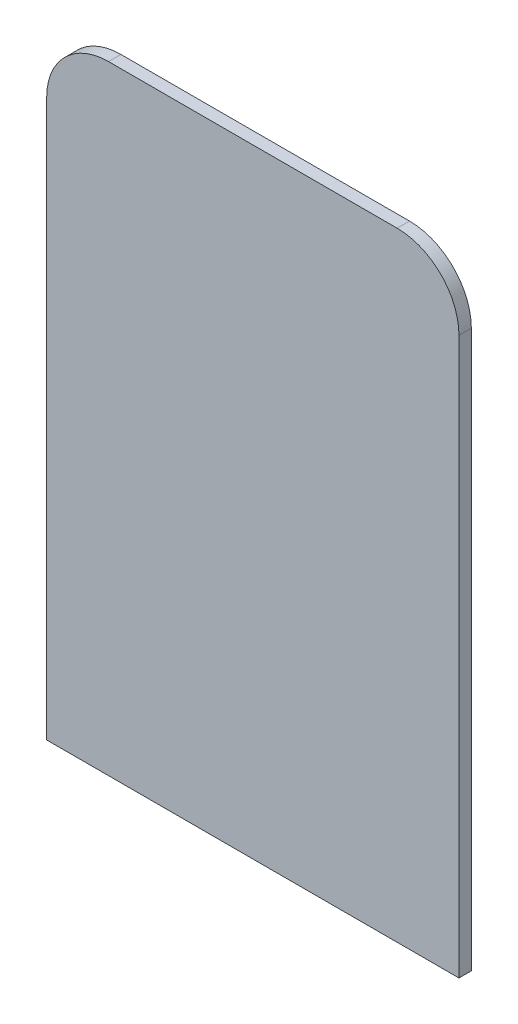
SolidWorks part; units mm, degrees
material "Acrylic (Medium-high impact)"
ref_plane "Front Plane" through (0, 0, 0) normal (0, 0, 1) x (1, 0, 0)
ref_plane "Top Plane" through (0, 0, 0) normal (0, 1, 0) x (1, 0, 0)
ref_plane "Right Plane" through (0, 0, 0) normal (1, 0, 0) x (0, 0, -1)
sketch "Sketch1" [suppressed] plane through (0, 0, 0) normal (0, 1, 0) x (1, 0, 0)
  line L1 (-60, -30) -> (60, -30)
  line L2 (-60, -30) -> (-60, 30)
  line L3 (-60, 30) -> (60, 30)
  line L4 (60, -30) -> (60, 30)
  line L5 (-60, -30) -> (60, 30) construction
  line L6 (-60, 30) -> (60, -30) construction
  point P0 (0, 0)
  dimension "D1" = 120
  dimension "D2" = 60
extrude "Boss-Extrude1" [suppressed] add sketch "Sketch1" along normal blind 3
sketch "Sketch2" [suppressed] plane through (0, 0, 0) normal (1, 0, 0) x (0, 0, -1)
  line L1 (-25, 7.5) -> (25, 7.5)
  line L2 (-25, 7.5) -> (-25, -7.5)
  line L3 (-25, -7.5) -> (25, -7.5)
  line L4 (25, 7.5) -> (25, -7.5)
  line L5 (-25, 7.5) -> (25, -7.5) construction
  line L6 (-25, -7.5) -> (25, 7.5) construction
  point P0 (0, 0)
  dimension "D1" = 60
  dimension "D2" = 15
extrude "Boss-Extrude2" [suppressed] add sketch "Sketch2" along normal blind 3
sketch "Sketch3" [suppressed] plane through (0, 3, 0) normal (0, 1, 0) x (1, 0, 0)
  line L0 (60, 30) -> (-60, 30) construction
  line L1 (-52, 30) -> (-43, 30)
  line L2 (-52, 30) -> (-52, 27)
  line L3 (-52, 27) -> (-43, 27)
  line L4 (-43, 30) -> (-43, 27)
  line L5 (-60, 30) -> (-60, -30) construction
  line L6 (-33, 30) -> (-24, 30)
  line L7 (-33, 30) -> (-33, 27)
  line L8 (-33, 27) -> (-24, 27)
  line L9 (-24, 30) -> (-24, 27)
  line L10 (-33, -27) -> (-24, -27)
  line L11 (-33, -27) -> (-33, -30)
  line L12 (-33, -30) -> (-24, -30)
  line L13 (-24, -27) -> (-24, -30)
  line L14 (-52, -27) -> (-43, -27)
  line L15 (-52, -27) -> (-52, -30)
  line L16 (-52, -30) -> (-43, -30)
  line L17 (-43, -27) -> (-43, -30)
  line L18 (-60, -30) -> (60, -30) construction
  line L43 (-14, 30) -> (-5, 30)
  line L44 (-14, 30) -> (-14, 27)
  line L45 (-14, 27) -> (-5, 27)
  line L46 (-5, 30) -> (-5, 27)
  line L47 (5, 30) -> (14, 30)
  line L48 (5, 30) -> (5, 27)
  line L49 (5, 27) -> (14, 27)
  line L50 (14, 30) -> (14, 27)
  line L51 (24, 30) -> (33, 30)
  line L52 (24, 30) -> (24, 27)
  line L53 (24, 27) -> (33, 27)
  line L54 (33, 30) -> (33, 27)
  line L59 (-14, -27) -> (-5, -27)
  line L60 (-14, -27) -> (-14, -30)
  line L61 (-14, -30) -> (-5, -30)
  line L62 (-5, -27) -> (-5, -30)
  line L63 (5, -27) -> (14, -27)
  line L64 (5, -27) -> (5, -30)
  line L65 (5, -30) -> (14, -30)
  line L66 (14, -27) -> (14, -30)
  line L67 (24, -27) -> (33, -27)
  line L68 (24, -27) -> (24, -30)
  line L69 (24, -30) -> (33, -30)
  line L70 (33, -27) -> (33, -30)
  line L71 (43, 30) -> (52, 30)
  line L72 (43, 30) -> (43, 27)
  line L73 (43, 27) -> (52, 27)
  line L74 (52, 30) -> (52, 27)
  line L83 (43, -27) -> (52, -27)
  line L84 (43, -27) -> (43, -30)
  line L85 (43, -30) -> (52, -30)
  line L86 (52, -27) -> (52, -30)
  line L105 (60, -30) -> (60, 30) construction
  dimension "D1" = 8
  dimension "D2" = 9
  dimension "D5" = 3
  dimension "D6" = 10
  dimension "D7" = 8
  dimension "D3" = 6
  dimension "D4" = 2
extrude "Cut-Extrude1" [suppressed] cut sketch "Sketch3" against normal blind 3
sketch "Sketch5" [suppressed] plane through (0, 0, 0) normal (-1, 0, 0) x (0, 0, 1)
  line L0 (30, -7.5) -> (-30, -7.5) construction
  line L1 (-30, 7.5) -> (-27, 7.5)
  line L2 (-30, 7.5) -> (-30, -7.5)
  line L3 (-30, -7.5) -> (-27, -7.5)
  line L4 (-27, 7.5) -> (-27, -7.5)
  line L5 (-12.5, -7.5) -> (-7.5, -7.5)
  line L6 (30, 7.5) -> (27, 7.5)
  line L7 (30, 7.5) -> (30, -7.5)
  line L8 (30, -7.5) -> (27, -7.5)
  line L9 (27, 7.5) -> (27, -7.5)
  line L10 (-22.5, -7.5) -> (-17.5, -7.5)
  line L11 (-22.5, -7.5) -> (-22.5, -4.5)
  line L12 (-22.5, -4.5) -> (-17.5, -4.5)
  line L13 (-17.5, -7.5) -> (-17.5, -4.5)
  line L14 (-12.5, -7.5) -> (-12.5, -4.5)
  line L15 (-12.5, -4.5) -> (-7.5, -4.5)
  line L16 (-7.5, -7.5) -> (-7.5, -4.5)
  line L17 (-2.5, -7.5) -> (2.5, -7.5)
  line L18 (-2.5, -7.5) -> (-2.5, -4.5)
  line L19 (-2.5, -4.5) -> (2.5, -4.5)
  line L20 (2.5, -7.5) -> (2.5, -4.5)
  line L21 (7.5, -7.5) -> (12.5, -7.5)
  line L22 (7.5, -7.5) -> (7.5, -4.5)
  line L23 (7.5, -4.5) -> (12.5, -4.5)
  line L24 (12.5, -7.5) -> (12.5, -4.5)
  line L25 (-12.5, 4.5) -> (-7.5, 4.5)
  line L26 (-12.5, 4.5) -> (-12.5, 7.5)
  line L27 (-12.5, 7.5) -> (-7.5, 7.5)
  line L28 (-7.5, 4.5) -> (-7.5, 7.5)
  line L29 (-2.5, 4.5) -> (2.5, 4.5)
  line L30 (-2.5, 4.5) -> (-2.5, 7.5)
  line L31 (-2.5, 7.5) -> (2.5, 7.5)
  line L32 (2.5, 4.5) -> (2.5, 7.5)
  line L33 (7.5, 4.5) -> (12.5, 4.5)
  line L34 (7.5, 4.5) -> (7.5, 7.5)
  line L35 (7.5, 7.5) -> (12.5, 7.5)
  line L36 (12.5, 4.5) -> (12.5, 7.5)
  line L37 (-22.5, 4.5) -> (-17.5, 4.5)
  line L38 (-22.5, 4.5) -> (-22.5, 7.5)
  line L39 (-22.5, 7.5) -> (-17.5, 7.5)
  line L40 (-17.5, 4.5) -> (-17.5, 7.5)
  line L41 (-30, 7.5) -> (30, 7.5) construction
  line L42 (17.5, -7.5) -> (22.5, -7.5)
  line L43 (17.5, -7.5) -> (17.5, -4.5)
  line L44 (17.5, -4.5) -> (22.5, -4.5)
  line L45 (22.5, -7.5) -> (22.5, -4.5)
  line L46 (17.5, 4.5) -> (22.5, 4.5)
  line L47 (17.5, 4.5) -> (17.5, 7.5)
  line L48 (17.5, 7.5) -> (22.5, 7.5)
  line L49 (22.5, 4.5) -> (22.5, 7.5)
  dimension "D1" = 3
  dimension "D2" = 3
  dimension "D3" = 3
  dimension "D4" = 5
  dimension "D8" = 5
  dimension "D9" = 4.5
  dimension "D6" = 5
  dimension "D7" = 2
extrude "Cut-Extrude2" [suppressed] cut sketch "Sketch5" against normal blind 3
sketch "Sketch6" [suppressed] plane through (0, 0, 0) normal (-1, 0, 0) x (0, 0, 1)
  line L0 (3, -2.5) -> (9.5, -2.5)
  line L1 (9.5, -2.5) -> (9.5, -3.26)
  line L2 (9.5, -3.26) -> (14.5, -3.26)
  line L3 (14.5, -3.26) -> (14.5, -2.5)
  line L4 (14.5, -2.5) -> (21, -2.5)
  line L5 (21, -2.5) -> (21, -0.75)
  line L6 (21, -0.75) -> (16, -0.75)
  line L7 (16, -0.75) -> (16, 2.25)
  line L8 (16, 2.25) -> (8, 2.25)
  line L9 (8, 2.25) -> (8, -0.75)
  line L10 (8, -0.75) -> (3, -0.75)
  line L11 (3, -0.75) -> (3, -2.5)
  line L12 (12, -3.26) -> (12, 2.25) construction
  line L13 (12, -0.505) -> (12.4437, -0.505) construction
  line L14 (17.5, -4.5) -> (12.5, -4.5) construction
  line L15 (22, 7.5) -> (22, -7.5) construction
  dimension "D1" = 5
  dimension "D2" = 18
  dimension "D3" = 8
  dimension "D4" = 1.75
  dimension "D5" = 5.51
  dimension "D6" = 4.75
  dimension "D7" = 2
  dimension "D8" = 1
extrude "Cut-Extrude3" [suppressed] cut sketch "Sketch6" against normal blind 3
sketch "Sketch7" [suppressed] plane through (0, 3, 0) normal (0, 1, 0) x (1, 0, 0)
  line L0 (-60, 30) -> (-60, -30) construction
  line L1 (-60, 17.5) -> (-57, 17.5)
  line L2 (-60, 17.5) -> (-60, 12.5)
  line L3 (-60, 12.5) -> (-57, 12.5)
  line L4 (-57, 17.5) -> (-57, 12.5)
  line L5 (-52, 27) -> (-43, 27) construction
  line L6 (-60, 27) -> (-57, 27)
  line L7 (57, 17.5) -> (60, 17.5)
  line L8 (57, 17.5) -> (57, 12.5)
  line L9 (57, 12.5) -> (60, 12.5)
  line L10 (60, 17.5) -> (60, 12.5)
  line L11 (57, 7.5) -> (60, 7.5)
  line L12 (57, 7.5) -> (57, 2.5)
  line L13 (57, 2.5) -> (60, 2.5)
  line L14 (60, 7.5) -> (60, 2.5)
  line L15 (57, -2.5) -> (60, -2.5)
  line L16 (57, -2.5) -> (57, -7.5)
  line L17 (57, -7.5) -> (60, -7.5)
  line L18 (60, -2.5) -> (60, -7.5)
  line L23 (-60, 7.5) -> (-57, 7.5)
  line L24 (-60, 7.5) -> (-60, 2.5)
  line L25 (-60, 2.5) -> (-57, 2.5)
  line L26 (-57, 7.5) -> (-57, 2.5)
  line L27 (-60, -2.5) -> (-57, -2.5)
  line L28 (-60, -2.5) -> (-60, -7.5)
  line L29 (-60, -7.5) -> (-57, -7.5)
  line L30 (-57, -2.5) -> (-57, -7.5)
  line L35 (60, -30) -> (60, 30) construction
  line L36 (-60, -12.5) -> (-57, -12.5)
  line L45 (-60, 27) -> (-60, 22.5)
  line L46 (-60, 22.5) -> (-57, 22.5)
  line L47 (-57, 27) -> (-57, 22.5)
  line L48 (57, 27) -> (60, 27)
  line L49 (57, 27) -> (57, 22.5)
  line L50 (57, 22.5) -> (60, 22.5)
  line L51 (60, 27) -> (60, 22.5)
  line L52 (57, -22.5) -> (60, -22.5)
  line L53 (57, -22.5) -> (57, -27)
  line L54 (57, -27) -> (60, -27)
  line L55 (60, -22.5) -> (60, -27)
  line L56 (-60, -22.5) -> (-57, -22.5)
  line L57 (-60, -22.5) -> (-60, -27)
  line L58 (-60, -27) -> (-57, -27)
  line L59 (-57, -22.5) -> (-57, -27)
  line L60 (-43, -27) -> (-52, -27) construction
  line L61 (-60, -12.5) -> (-60, -17.5)
  line L62 (-60, -17.5) -> (-57, -17.5)
  line L63 (-57, -12.5) -> (-57, -17.5)
  line L64 (57, -12.5) -> (60, -12.5)
  line L65 (57, -12.5) -> (57, -17.5)
  line L66 (57, -17.5) -> (60, -17.5)
  line L67 (60, -12.5) -> (60, -17.5)
  point P24 (-58.5, 17.5)
  dimension "D1" = 3
  dimension "D2" = 5
  dimension "D3" = 4.5
  dimension "D6" = 5
  dimension "D7" = 5
  dimension "D8" = 2
  dimension "D4" = 2
  dimension "D5" = 4
  dimension "D9" = 2
extrude "Cut-Extrude4" [suppressed] cut sketch "Sketch7" against normal blind 3
sketch "Sketch8" [suppressed] plane through (0, 3, 0) normal (0, 1, 0) x (1, 0, 0)
  line L0 (0, 0) -> (0, 14.25) construction
  line L1 (-50, 18) -> (50, 18)
  line L2 (-50, 18) -> (-50, 14.25)
  line L3 (-50, 14.25) -> (50, 14.25)
  line L4 (50, 18) -> (50, 14.25)
  line L5 (-33, 27) -> (-24, 27) construction
  line L6 (-50, 16.125) -> (-12.8184, 16.125) construction
  line L8 (-5, -27) -> (-14, -27) construction
  circle A0 centre (0, -18) radius 5.875
  dimension "D2" = 9
  dimension "D3" = 11.75
  dimension "D1" = 3.75
  dimension "D4" = 9
  dimension "D5" = 100
extrude "Cut-Extrude5" [suppressed] cut sketch "Sketch8" against normal blind 3
sketch "Sketch9" [suppressed] plane through (0, 3, 0) normal (0, 1, 0) x (1, 0, 0)
  line L0 (-60, 2.5) -> (-60, -2.5) construction
  line L1 (-16, -17) -> (-13, -17)
  line L2 (-16, -17) -> (-16, -22)
  line L3 (-16, -22) -> (-13, -22)
  line L4 (-13, -17) -> (-13, -22)
  line L5 (-24, -27) -> (-33, -27) construction
  line L6 (-16, -7) -> (-13, -7)
  line L7 (-16, -7) -> (-16, -12)
  line L8 (-16, -12) -> (-13, -12)
  line L9 (-13, -7) -> (-13, -12)
  line L10 (-16, 3) -> (-13, 3)
  line L11 (-16, 3) -> (-16, -2)
  line L12 (-16, -2) -> (-13, -2)
  line L13 (-13, 3) -> (-13, -2)
  line L14 (13, -17) -> (16, -17)
  line L15 (13, -17) -> (13, -22)
  line L16 (13, -22) -> (16, -22)
  line L17 (16, -17) -> (16, -22)
  line L18 (13, -7) -> (16, -7)
  line L19 (13, -7) -> (13, -12)
  line L20 (13, -12) -> (16, -12)
  line L21 (16, -7) -> (16, -12)
  line L22 (13, 3) -> (16, 3)
  line L23 (13, 3) -> (13, -2)
  line L24 (13, -2) -> (16, -2)
  line L25 (16, 3) -> (16, -2)
  line L26 (-16, 13) -> (-13, 13)
  line L27 (-16, 13) -> (-16, 8)
  line L28 (-16, 8) -> (-13, 8)
  line L29 (-13, 13) -> (-13, 8)
  line L30 (13, 13) -> (16, 13)
  line L31 (13, 13) -> (13, 8)
  line L32 (13, 8) -> (16, 8)
  line L33 (16, 13) -> (16, 8)
  line L34 (-14, 27) -> (-5, 27) construction
  line L35 (-13, 27) -> (-16, 27)
  line L36 (-13, 27) -> (-13, 24)
  line L37 (-13, 24) -> (-16, 24)
  line L38 (-16, 27) -> (-16, 24)
  line L39 (5, 27) -> (14, 27) construction
  line L40 (16, 27) -> (13, 27)
  line L41 (16, 27) -> (16, 24)
  line L42 (16, 24) -> (13, 24)
  line L43 (13, 27) -> (13, 24)
  dimension "D1" = 44
  dimension "D2" = 3
  dimension "D3" = 5
  dimension "D4" = 5
  dimension "D6" = 5
  dimension "D8" = 13
  dimension "D9" = 13
  dimension "D10" = 3
  dimension "D5" = 4
  dimension "D7" = 2
extrude "Cut-Extrude6" [suppressed] cut sketch "Sketch9" against normal blind 3
sketch "Sketch10" [suppressed] plane through (0, 0, 0) normal (1, 0, 0) x (0, 0, -1)
  line L1 (30, -7.5) -> (-30, -7.5)
  line L2 (30, -7.5) -> (30, 7.5)
  line L3 (30, 7.5) -> (-30, 7.5)
  line L4 (-30, -7.5) -> (-30, 7.5)
  line L5 (30, -7.5) -> (-30, 7.5) construction
  line L6 (30, 7.5) -> (-30, -7.5) construction
  point P0 (0, 0)
  dimension "D1" = 60
  dimension "D2" = 15
extrude "Boss-Extrude3" [suppressed] add sketch "Sketch10" along normal blind 3
sketch "Sketch25" [suppressed] plane through (0, 0, 0) normal (-1, 0, 0) x (0, 0, 1)
  line L0 (30, -7.5) -> (-30, -7.5) construction
  line L1 (-30, 7.5) -> (-24, 7.5)
  line L2 (-30, 7.5) -> (-30, -7.5)
  line L3 (-30, -7.5) -> (-24, -7.5)
  line L4 (-24, 7.5) -> (-24, -7.5)
  dimension "D1" = 6
extrude "Cut-Extrude17" [suppressed] cut sketch "Sketch25" against normal blind 3
sketch "Sketch11" [suppressed] plane through (0, 0, 0) normal (-1, 0, 0) x (0, 0, 1)
  line L0 (-24, 7.5) -> (30, 7.5) construction
  line L1 (30, 7.5) -> (25, 7.5)
  line L2 (30, 7.5) -> (30, 4.5)
  line L3 (30, 4.5) -> (25, 4.5)
  line L4 (25, 7.5) -> (25, 4.5)
  line L5 (-10, 7.5) -> (-15, 7.5)
  line L6 (20, 7.5) -> (15, 7.5)
  line L7 (20, 7.5) -> (20, 4.5)
  line L8 (20, 4.5) -> (15, 4.5)
  line L9 (15, 7.5) -> (15, 4.5)
  line L10 (20, -4.5) -> (15, -4.5)
  line L11 (20, -4.5) -> (20, -7.5)
  line L12 (20, -7.5) -> (15, -7.5)
  line L13 (15, -4.5) -> (15, -7.5)
  line L14 (30, -4.5) -> (25, -4.5)
  line L15 (30, -4.5) -> (30, -7.5)
  line L16 (30, -7.5) -> (25, -7.5)
  line L17 (25, -4.5) -> (25, -7.5)
  line L18 (30, -7.5) -> (-24, -7.5) construction
  line L19 (10, 7.5) -> (5, 7.5)
  line L20 (10, 7.5) -> (10, 4.5)
  line L21 (10, 4.5) -> (5, 4.5)
  line L22 (5, 7.5) -> (5, 4.5)
  line L23 (0, 7.5) -> (-5, 7.5)
  line L24 (0, 7.5) -> (0, 4.5)
  line L25 (0, 4.5) -> (-5, 4.5)
  line L26 (-5, 7.5) -> (-5, 4.5)
  line L27 (10, -4.5) -> (5, -4.5)
  line L28 (10, -4.5) -> (10, -7.5)
  line L29 (10, -7.5) -> (5, -7.5)
  line L30 (5, -4.5) -> (5, -7.5)
  line L31 (0, -4.5) -> (-5, -4.5)
  line L32 (0, -4.5) -> (0, -7.5)
  line L33 (0, -7.5) -> (-5, -7.5)
  line L34 (-5, -4.5) -> (-5, -7.5)
  line L35 (30, 7.5) -> (30, -7.5) construction
  line L36 (-10, 7.5) -> (-10, 4.5)
  line L37 (-10, 4.5) -> (-15, 4.5)
  line L38 (-15, 7.5) -> (-15, 4.5)
  line L39 (-10, -4.5) -> (-15, -4.5)
  line L40 (-10, -4.5) -> (-10, -7.5)
  line L41 (-10, -7.5) -> (-15, -7.5)
  line L42 (-15, -4.5) -> (-15, -7.5)
  dimension "D1" = 3
  dimension "D3" = 5
  dimension "D6" = 5
  dimension "D4" = 5
  dimension "D5" = 2
extrude "Cut-Extrude7" [suppressed] cut sketch "Sketch11" against normal blind 3
sketch "Sketch24" [suppressed] plane through (0, 0, 0) normal (-1, 0, 0) x (0, 0, 1)
  line L1 (-21, 7.5) -> (-14, 7.5)
  line L2 (-21, 7.5) -> (-21, 4.5)
  line L3 (-21, 4.5) -> (-14, 4.5)
  line L4 (-14, 7.5) -> (-14, 4.5)
  line L7 (-21, -7.5) -> (-14, -7.5)
  line L8 (-21, -7.5) -> (-21, -4.5)
  line L9 (-21, -4.5) -> (-14, -4.5)
  line L10 (-14, -7.5) -> (-14, -4.5)
  line L13 (15, 4.5) -> (20, 4.5) construction
  line L14 (20, -4.5) -> (15, -4.5) construction
  line L17 (25, -7.5) -> (20, -7.5) construction
  line L18 (20, 7.5) -> (25, 7.5) construction
  line L19 (-24, -7.5) -> (-24, 7.5) construction
  dimension "D1" = 3
  dimension "D2" = 7
extrude "Cut-Extrude16" [suppressed] cut sketch "Sketch24" against normal blind 3
sketch "Sketch13" [suppressed] plane through (3, 0, 0) normal (1, 0, 0) x (0, 0, -1)
  line L0 (24, -7.5) -> (24, 7.5) construction
  line L1 (20.4581, -3.75) -> (17.7081, -3.75)
  line L2 (20.4581, -3.75) -> (20.4581, -8.4952)
  line L3 (20.4581, -8.4952) -> (9.9581, -8.4952)
  line L4 (9.9581, -3.75) -> (9.9581, -8.4952)
  line L5 (24, 7.5) -> (10, 7.5) construction
  line L6 (17.7081, -3.75) -> (17.7081, -2.3)
  line L7 (17.7081, -2.3) -> (12.7081, -2.3)
  line L8 (12.7081, -2.3) -> (12.7081, -3.75)
  line L9 (12.7081, -3.75) -> (9.9581, -3.75)
  line L10 (15.2081, -2.3) -> (13.125, 7.5) construction
  line L12 (0, -4.5) -> (5, -4.5) construction
  dimension "D5" = 10.5
  dimension "D2" = 0.75
  dimension "D3" = 2.2
  dimension "D4" = 5
  dimension "D6" = 2.75
  dimension "D7" = 3.5419
  dimension "D8" = 102
  dimension "D1" = 10.875
extrude "Cut-Extrude9" [suppressed] cut sketch "Sketch13" against normal blind 3
sketch "Sketch14" [suppressed] plane through (3, 0, 0) normal (1, 0, 0) x (0, 0, -1)
  line L0 (-20, 4.5) -> (-20, 3.5)
  line L1 (-15, 4.5) -> (-15, 3.5)
  line L2 (-20, 4.5) -> (-15, 4.5)
  arc A0 (-20, 3.5) -> (-15, 3.5) centre (-17.5, 3.5) ccw
  dimension "D1" = 1
extrude "Cut-Extrude10" [suppressed] cut sketch "Sketch14" against normal blind 3
sketch "Sketch15" [suppressed] plane through (0, 0, 0) normal (0, 0, 1) x (1, 0, 0)
  line L1 (-60, -7.5) -> (60, -7.5)
  line L2 (-60, -7.5) -> (-60, 7.5)
  line L3 (-60, 7.5) -> (60, 7.5)
  line L4 (60, -7.5) -> (60, 7.5)
  line L5 (-60, -7.5) -> (60, 7.5) construction
  line L6 (-60, 7.5) -> (60, -7.5) construction
  point P0 (0, 0)
  dimension "D1" = 15
  dimension "D2" = 120
extrude "Boss-Extrude4" [suppressed] add sketch "Sketch15" along normal blind 3
sketch "Sketch16" [suppressed] plane through (0, 0, 3) normal (0, 0, 1) x (1, 0, 0)
  line L0 (60, 7.5) -> (-60, 7.5) construction
  line L1 (-60, 7.5) -> (-52, 7.5)
  line L2 (-60, 7.5) -> (-60, 4.5)
  line L3 (-60, 4.5) -> (-52, 4.5)
  line L4 (-52, 7.5) -> (-52, 4.5)
  line L5 (-43, 7.5) -> (-33, 7.5)
  line L6 (-43, 7.5) -> (-43, 4.5)
  line L7 (-43, 4.5) -> (-33, 4.5)
  line L8 (-33, 7.5) -> (-33, 4.5)
  line L9 (52, 7.5) -> (52, 4.5)
  line L10 (52, 7.5) -> (60, 7.5)
  line L11 (60, 7.5) -> (60, 4.5)
  line L12 (52, 4.5) -> (60, 4.5)
  line L13 (52, -4.5) -> (52, -7.5)
  line L14 (52, -4.5) -> (60, -4.5)
  line L15 (60, -4.5) -> (60, -7.5)
  line L16 (52, -7.5) -> (60, -7.5)
  line L17 (-60, -4.5) -> (-60, -7.5)
  line L18 (-60, -4.5) -> (-52, -4.5)
  line L19 (-52, -4.5) -> (-52, -7.5)
  line L20 (-60, -7.5) -> (-52, -7.5)
  line L21 (-60, -7.5) -> (60, -7.5) construction
  line L22 (60, -7.5) -> (60, 7.5) construction
  line L23 (-24, 7.5) -> (-24, 4.5)
  line L24 (-24, 7.5) -> (-14, 7.5)
  line L25 (-14, 7.5) -> (-14, 4.5)
  line L26 (-24, 4.5) -> (-14, 4.5)
  line L27 (-5, 7.5) -> (-5, 4.5)
  line L28 (-5, 7.5) -> (5, 7.5)
  line L29 (5, 7.5) -> (5, 4.5)
  line L30 (-5, 4.5) -> (5, 4.5)
  line L31 (14, 7.5) -> (14, 4.5)
  line L32 (14, 7.5) -> (24, 7.5)
  line L33 (24, 7.5) -> (24, 4.5)
  line L34 (14, 4.5) -> (24, 4.5)
  line L35 (33, 7.5) -> (33, 4.5)
  line L36 (33, 7.5) -> (43, 7.5)
  line L37 (43, 7.5) -> (43, 4.5)
  line L38 (33, 4.5) -> (43, 4.5)
  line L39 (-24, -4.5) -> (-24, -7.5)
  line L40 (-24, -4.5) -> (-14, -4.5)
  line L41 (-14, -4.5) -> (-14, -7.5)
  line L42 (-24, -7.5) -> (-14, -7.5)
  line L43 (-5, -4.5) -> (-5, -7.5)
  line L44 (-5, -4.5) -> (5, -4.5)
  line L45 (5, -4.5) -> (5, -7.5)
  line L46 (-5, -7.5) -> (5, -7.5)
  line L47 (14, -4.5) -> (14, -7.5)
  line L48 (14, -4.5) -> (24, -4.5)
  line L49 (24, -4.5) -> (24, -7.5)
  line L50 (14, -7.5) -> (24, -7.5)
  line L51 (33, -4.5) -> (33, -7.5)
  line L52 (33, -4.5) -> (43, -4.5)
  line L53 (43, -4.5) -> (43, -7.5)
  line L54 (33, -7.5) -> (43, -7.5)
  line L55 (-43, -4.5) -> (-43, -7.5)
  line L56 (-43, -4.5) -> (-33, -4.5)
  line L57 (-33, -4.5) -> (-33, -7.5)
  line L58 (-43, -7.5) -> (-33, -7.5)
  point P27 (-33, 6)
  dimension "D1" = 3
  dimension "D4" = 8
  dimension "D5" = 10
  dimension "D6" = 9
  dimension "D9" = 9
  dimension "D10" = 9
  dimension "D11" = 8
  dimension "D2" = 2
  dimension "D3" = 2
  dimension "D7" = 5
  dimension "D8" = 2
extrude "Cut-Extrude11" [suppressed] cut sketch "Sketch16" against normal blind 3
sketch "Sketch17" [suppressed] plane through (3, 0, 0) normal (1, 0, 0) x (0, 0, -1)
  line L0 (18.625, -2.5) -> (18.625, 4.5) construction
  line L1 (15.375, 11.8582) -> (-19.5274, 11.8582)
  line L2 (15.375, 11.8582) -> (15.375, -12.5837)
  line L3 (15.375, -12.5837) -> (-19.5274, -12.5837)
  line L4 (-19.5274, 11.8582) -> (-19.5274, -12.5837)
  dimension "D1" = 3.25
extrude "Cut-Extrude12" [suppressed] cut sketch "Sketch17" against normal blind 3
sketch "Sketch18" plane through (0, 0, 0) normal (0, 0, 1) x (1, 0, 0)
  line L1 (-50, -75) -> (50, -75)
  line L2 (-50, -75) -> (-50, 60)
  line L3 (-35, 75) -> (35, 75)
  line L4 (50, -75) -> (50, 60)
  line L5 (-50, -75) -> (50, 75) construction
  line L6 (-50, 75) -> (50, -75) construction
  arc A0 (50, 60) -> (35, 75) centre (35, 60) ccw
  arc A1 (-50, 60) -> (-35, 75) centre (-35, 60) cw
  point P0 (0, 0)
  dimension "D3" = 15
  dimension "D1" = 100
  dimension "D2" = 150
extrude "Boss-Extrude5" add sketch "Sketch18" along normal blind 3
sketch "Sketch19" [suppressed] plane through (0, 0, 0) normal (1, 0, 0) x (0, 0, -1)
  line L0 (2.5, 0.25) -> (2.5, 1.75)
  line L1 (5, -0.25) -> (-5, -0.25)
  line L2 (5, -0.25) -> (5, 0.25)
  line L3 (5, 0.25) -> (2.5, 0.25)
  line L4 (-5, -0.25) -> (-5, 0.25)
  line L5 (5, -0.25) -> (-5, 0.25) construction
  line L6 (5, 0.25) -> (-5, -0.25) construction
  line L7 (2.5, 1.75) -> (-2.5, 1.75)
  line L8 (-2.5, 1.75) -> (-2.5, 0.25)
  line L9 (-2.5, 0.25) -> (-5, 0.25)
  point P0 (0, 0)
  dimension "D1" = 0.5
  dimension "D2" = 10
  dimension "D3" = 2
  dimension "D4" = 5
extrude "Boss-Extrude6" [suppressed] add sketch "Sketch19" along normal blind 100
sketch "Sketch20" [suppressed] plane through (0, 0, 2.5) normal (0, 0, 1) x (1, 0, 0)
  line L0 (100, 1.75) -> (0, 1.75) construction
  line L1 (11.25, 1.75) -> (22.75, 1.75)
  line L2 (11.25, 1.75) -> (11.25, 0.25)
  line L3 (11.25, 0.25) -> (22.75, 0.25)
  line L4 (22.75, 1.75) -> (22.75, 0.25)
  line L5 (100, 0.25) -> (0, 0.25) construction
  line L6 (27.75, 1.75) -> (27.75, 0.25)
  line L7 (27.75, 1.75) -> (39.25, 1.75)
  line L8 (39.25, 1.75) -> (39.25, 0.25)
  line L9 (27.75, 0.25) -> (39.25, 0.25)
  line L10 (44.25, 1.75) -> (44.25, 0.25)
  line L11 (44.25, 1.75) -> (55.75, 1.75)
  line L12 (55.75, 1.75) -> (55.75, 0.25)
  line L13 (44.25, 0.25) -> (55.75, 0.25)
  line L14 (60.75, 1.75) -> (60.75, 0.25)
  line L15 (60.75, 1.75) -> (72.25, 1.75)
  line L16 (72.25, 1.75) -> (72.25, 0.25)
  line L17 (60.75, 0.25) -> (72.25, 0.25)
  line L18 (77.25, 1.75) -> (77.25, 0.25)
  line L19 (77.25, 1.75) -> (88.75, 1.75)
  line L20 (88.75, 1.75) -> (88.75, 0.25)
  line L21 (77.25, 0.25) -> (88.75, 0.25)
  line L23 (6.25, 0.25) -> (0, 0.25)
  line L24 (6.25, 0.25) -> (6.25, 1.75)
  line L25 (6.25, 1.75) -> (0, 1.75)
  line L26 (0, 0.25) -> (0, 1.75)
  line L27 (100, 1.75) -> (93.75, 1.75)
  line L28 (100, 1.75) -> (100, 0.25)
  line L29 (100, 0.25) -> (93.75, 0.25)
  line L30 (93.75, 1.75) -> (93.75, 0.25)
  dimension "D1" = 11.5
  dimension "D3" = 5
  dimension "D4" = 5
  dimension "D5" = 5
  dimension "D2" = 5
extrude "Cut-Extrude13" [suppressed] cut sketch "Sketch20" against normal blind 5
sketch "Sketch21" [suppressed] plane through (0, 0.25, 0) normal (0, 1, 0) x (1, 0, 0)
  line L0 (100, -5) -> (0, -5) construction
  line L1 (12.25, 0.55) -> (12.75, 0.55)
  line L2 (12.25, 0.55) -> (12.25, -0.25)
  line L3 (12.25, -0.25) -> (12.75, -0.25)
  line L4 (12.75, 0.55) -> (12.75, -0.25)
  line L5 (28.75, 0.55) -> (28.75, -0.25)
  line L6 (28.75, 0.55) -> (29.25, 0.55)
  line L7 (29.25, 0.55) -> (29.25, -0.25)
  line L8 (28.75, -0.25) -> (29.25, -0.25)
  line L9 (45.25, 0.55) -> (45.25, -0.25)
  line L10 (45.25, 0.55) -> (45.75, 0.55)
  line L11 (45.75, 0.55) -> (45.75, -0.25)
  line L12 (45.25, -0.25) -> (45.75, -0.25)
  line L13 (61.75, 0.55) -> (61.75, -0.25)
  line L14 (61.75, 0.55) -> (62.25, 0.55)
  line L15 (62.25, 0.55) -> (62.25, -0.25)
  line L16 (61.75, -0.25) -> (62.25, -0.25)
  line L17 (78.25, 0.55) -> (78.25, -0.25)
  line L18 (78.25, 0.55) -> (78.75, 0.55)
  line L19 (78.75, 0.55) -> (78.75, -0.25)
  line L20 (78.25, -0.25) -> (78.75, -0.25)
  line L21 (94.75, 0.55) -> (94.75, -0.25)
  line L22 (94.75, 0.55) -> (95.25, 0.55)
  line L23 (95.25, 0.55) -> (95.25, -0.25)
  line L24 (94.75, -0.25) -> (95.25, -0.25)
  line L25 (11.25, 2.5) -> (11.25, -2.5) construction
  line L26 (27.75, 2.5) -> (27.75, -2.5) construction
  dimension "D1" = 0.5
  dimension "D2" = 0.8
  dimension "D3" = 4.75
  dimension "D5" = 1
  dimension "D6" = 1
  dimension "D4" = 6
extrude "Boss-Extrude7" [suppressed] add sketch "Sketch21" along normal blind 0.3
sketch "Sketch22" [suppressed] plane through (0, 0, 0) normal (-1, 0, 0) x (0, 0, 1)
  line L0 (-11.25, 7.5) -> (-14.4383, -7.5)
  line L1 (-10, 7.5) -> (-5, 7.5) construction
  line L2 (-14.4383, -7.5) -> (-24, -7.5)
  line L3 (-24, -7.5) -> (-24, 7.5)
  line L4 (-24, 7.5) -> (-11.25, 7.5)
  line L6 (-21, 4.5) -> (-10, 4.5) construction
  line L7 (-5, -7.5) -> (-9.9581, -7.5) construction
  line L8 (-24, -7.5) -> (-24, 7.5) construction
  dimension "D2" = 102
  dimension "D1" = 12.75
extrude "Cut-Extrude14" [suppressed] cut sketch "Sketch22" against normal blind 3
sketch "Sketch23" [suppressed] plane through (0, 0, 0) normal (-1, 0, 0) x (0, 0, 1)
  line L0 (-16.4823, 7.5) -> (-19.6707, -7.5)
  line L1 (-19.6707, -7.5) -> (30, -7.5)
  line L2 (30, -7.5) -> (30, 7.5)
  line L3 (30, 7.5) -> (-16.4823, 7.5)
  line L4 (30, 4.5) -> (30, -4.5) construction
  line L5 (10, 7.5) -> (15, 7.5) construction
  line L6 (15, -7.5) -> (10, -7.5) construction
  line L7 (25, 4.5) -> (30, 4.5) construction
  line L8 (-17.12, 4.5) -> (-26.0911, 4.5) construction
  line L11 (-24, -7.5) -> (-24, 7.5) construction
  dimension "D1" = 102
  dimension "D2" = 9
extrude "Cut-Extrude15" [suppressed] cut sketch "Sketch23" against normal blind 3
sketch "Sketch26" [suppressed] plane through (0, 0, 0) normal (0, 1, 0) x (1, 0, 0)
  line L1 (-13, -10) -> (13, -10)
  line L2 (-13, -10) -> (-13, 10)
  line L3 (-13, 10) -> (13, 10)
  line L4 (13, -10) -> (13, 10)
  line L5 (-13, -10) -> (13, 10) construction
  line L6 (-13, 10) -> (13, -10) construction
  point P0 (0, 0)
  dimension "D1" = 26
  dimension "D2" = 20
extrude "Boss-Extrude8" [suppressed] add sketch "Sketch26" along normal blind 3
sketch "Sketch27" [suppressed] plane through (0, 3, 0) normal (0, 1, 0) x (1, 0, 0)
  line L0 (0, 3.375) -> (0, 10) construction
  line L1 (0, -5.375) -> (0, 3.375) construction
  line L2 (-6, -7) -> (6, -7) construction
  line L3 (-6, -7) -> (-6, 5) construction
  line L4 (-6, 5) -> (6, 5) construction
  line L5 (6, -7) -> (6, 5) construction
  line L6 (-6, -7) -> (6, 5) construction
  line L7 (-6, 5) -> (6, -7) construction
  line L8 (13, 10) -> (-13, 10) construction
  line L9 (-13, -10) -> (13, -10) construction
  circle A0 centre (0, 3.375) radius 0.875
  circle A1 centre (0, -5.375) radius 0.875
  point P5 (0, -1)
  dimension "D3" = 1.75
  dimension "D1" = 12
  dimension "D2" = 12
  dimension "D4" = 8.75
  dimension "D5" = 9
extrude "Cut-Extrude18" [suppressed] cut sketch "Sketch27" against normal blind 3
sketch "Sketch28" [suppressed] plane through (0, 3, 0) normal (0, 1, 0) x (1, 0, 0)
  line L0 (0, -13.625) -> (0, 0) construction
  line L1 (0, -22.375) -> (0, -13.625) construction
  line L2 (-6, -24) -> (6, -24) construction
  line L3 (-6, -24) -> (-6, -12) construction
  line L4 (-6, -12) -> (6, -12) construction
  line L5 (6, -24) -> (6, -12) construction
  line L6 (-6, -24) -> (6, -12) construction
  line L7 (-6, -12) -> (6, -24) construction
  line L8 (-5, -27) -> (-14, -27) construction
  circle A0 centre (0, -13.625) radius 0.875
  circle A1 centre (0, -22.375) radius 0.875
  point P5 (0, -18)
  dimension "D3" = 1.75
  dimension "D1" = 12
  dimension "D2" = 12
  dimension "D4" = 8.75
  dimension "D5" = 9
extrude "Cut-Extrude19" [suppressed] cut sketch "Sketch28" against normal blind 3
equation "\"TotalWidth\"=120"
equation "\"D1@Sketch1\"=\"TotalWidth\""
equation "\"BottomDepth\"=60"
equation "\"D1@Sketch2\"=\"BottomDepth\""
equation "\"Height\"=15"
equation "\"D2@Sketch2\"=\"Height\""
equation "\"D2@Sketch10\"=\"Height\""
equation "\"D1@Sketch15\"=\"Height\""
equation "\"D2@Sketch15\"=\"TotalWidth\""
equation "\"D2@Sketch1\"=\"BottomDepth\""
equation "\"D1@Sketch10\"=\"BottomDepth\""
equation "\"NamePlateTiltAngle\"=102"
equation "\"D2@Sketch22\"=\"NamePlateTiltAngle\""
equation "\"D1@Sketch23\"=\"NamePlateTiltAngle\""
equation "\"LedSlotDepth\"=9"
equation "\"D2@Sketch8\"=\"LedSlotDepth\""
equation "\"D2@Sketch23\"=\"LedSlotDepth\""
equation "\"SlotThickness\"=3.75"
equation "\"D1@Sketch8\"=\"SlotThickness\""
equation "\"D1@Sketch22\"=\"LedSlotDepth\"+\"SlotThickness\""
equation "\"D8@Sketch13\"=\"NamePlateTiltAngle\""
equation "\"D1@Sketch13\"=\"LedSlotDepth\"+(\"SlotThickness\"/2)"
equation "\"ButtonDepth\"=9"
equation "\"D5@Sketch27\"=\"ButtonDepth\""
equation "\"D4@Sketch8\"=\"ButtonDepth\""
equation "\"D5@Sketch28\"=\"ButtonDepth\""
